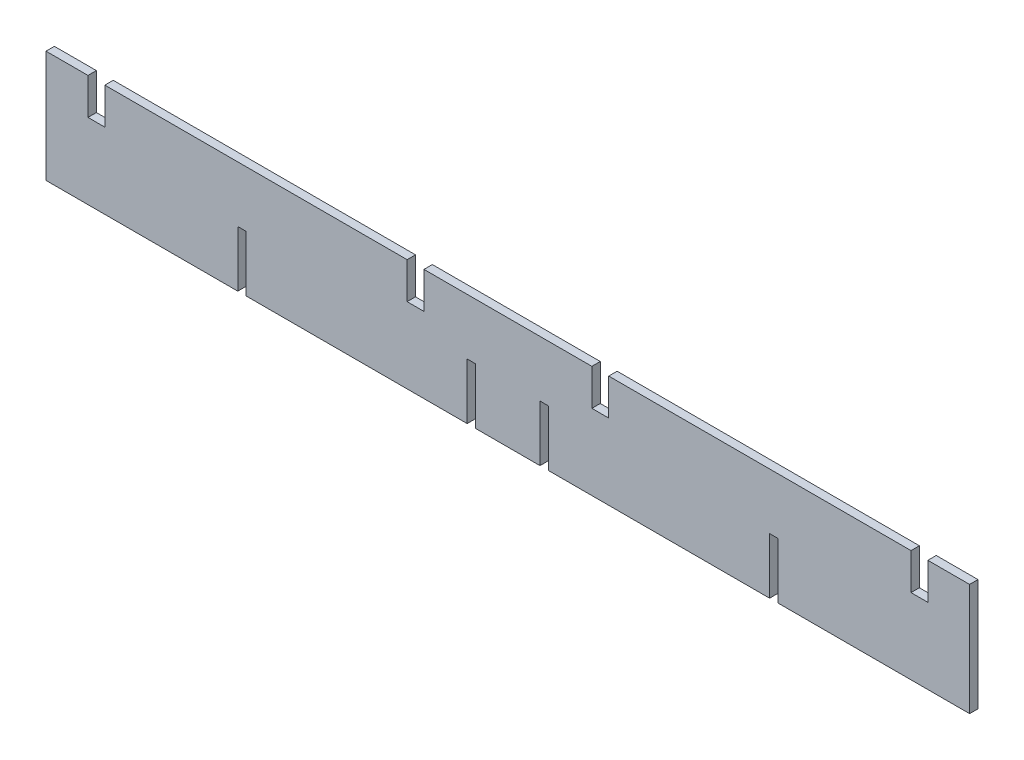
SolidWorks part; units mm, degrees
ref_plane "Front Plane" through (0, 0, 0) normal (0, 0, 1) x (1, 0, 0)
ref_plane "Top Plane" through (0, 0, 0) normal (0, 1, 0) x (1, 0, 0)
ref_plane "Right Plane" through (0, 0, 0) normal (1, 0, 0) x (0, 0, -1)
sketch "Sketch1" plane through (0, 0, 0) normal (0, 0, 1) x (1, 0, 0)
  line L1 (-330, 40) -> (330, 40)
  line L2 (-330, 40) -> (-330, -40)
  line L3 (-330, -40) -> (330, -40)
  line L4 (330, 40) -> (330, -40)
  line L5 (-330, 40) -> (330, -40) construction
  line L6 (-330, -40) -> (330, 40) construction
  point P0 (0, 0)
  dimension "D1" = 660
  dimension "D2" = 80
extrude "Boss-Extrude1" add sketch "Sketch1" along normal blind 6
sketch "Sketch2" plane through (0, 0, 6) normal (0, 0, 1) x (1, 0, 0)
  line L0 (-300, 40) -> (-300, 14)
  line L1 (330, 40) -> (-330, 40) construction
  line L2 (-300, 14) -> (-287.96, 14)
  line L3 (-287.96, 14) -> (-287.96, 40)
  line L4 (-287.96, 40) -> (-300, 40)
  line L5 (-330, 40) -> (-330, -40) construction
  line L6 (-71.96, 40) -> (-59.92, 40)
  line L7 (-71.96, 40) -> (-71.96, 14)
  line L8 (-71.96, 14) -> (-59.92, 14)
  line L9 (-59.92, 40) -> (-59.92, 14)
  line L10 (60.08, 40) -> (72.12, 40)
  line L11 (60.08, 40) -> (60.08, 14)
  line L12 (60.08, 14) -> (72.12, 14)
  line L13 (72.12, 40) -> (72.12, 14)
  line L14 (288.12, 40) -> (300.16, 40)
  line L15 (288.12, 40) -> (288.12, 14)
  line L16 (288.12, 14) -> (300.16, 14)
  line L17 (300.16, 40) -> (300.16, 14)
  line L18 (330, -40) -> (330, 40) construction
  dimension "D1" = 26
  dimension "D2" = 26
  dimension "D3" = 26
  dimension "D4" = 26
  dimension "D5" = 12.04
  dimension "D6" = 12.04
  dimension "D7" = 12.04
  dimension "D8" = 12.04
  dimension "D9" = 30
  dimension "D10" = 216
  dimension "D11" = 120
  dimension "D12" = 29.84
extrude "Cut-Extrude1" cut sketch "Sketch2" against normal through all
sketch "Sketch3" plane through (0, 0, 6) normal (0, 0, 1) x (1, 0, 0)
  line L0 (0, 0) -> (0, 67.8569) construction
  line L3 (-29.04, 0) -> (-23, 0)
  line L8 (23, 0) -> (29.04, 0)
  line L12 (-29.04, 0) -> (-29.04, -40)
  line L13 (-330, -40) -> (330, -40) construction
  line L14 (-29.04, -40) -> (-23, -40)
  line L15 (-23, -40) -> (-23, 0)
  line L16 (23, 0) -> (23, -40)
  line L17 (23, -40) -> (29.04, -40)
  line L18 (29.04, -40) -> (29.04, 0)
  dimension "D1" = 6.04
  dimension "D2" = 6.04
  dimension "D3" = 40
  dimension "D4" = 40
  dimension "D5" = 23
  dimension "D6" = 23
extrude "Cut-Extrude2" cut sketch "Sketch3" against normal through all
sketch "Sketch4" plane through (0, 0, 6) normal (0, 0, 1) x (1, 0, 0)
  line L0 (-330, -40) -> (-29.04, -40) construction
  line L1 (-186.92, -40) -> (-192.96, -40)
  line L2 (-186.92, -40) -> (-186.92, 0)
  line L3 (-186.92, 0) -> (-192.96, 0)
  line L4 (-192.96, -40) -> (-192.96, 0)
  line L5 (29.04, -40) -> (330, -40) construction
  line L6 (193.12, -40) -> (187.08, -40)
  line L7 (193.12, -40) -> (193.12, 0)
  line L8 (193.12, 0) -> (187.08, 0)
  line L9 (187.08, -40) -> (187.08, 0)
  line L10 (-287.96, 14) -> (-287.96, 40) construction
  line L12 (288.12, 40) -> (288.12, 14) construction
  dimension "D1" = 40
  dimension "D2" = 6.04
  dimension "D3" = 95
  dimension "D4" = 40
  dimension "D5" = 6.04
  dimension "D6" = 95
extrude "Cut-Extrude3" cut sketch "Sketch4" against normal through all
